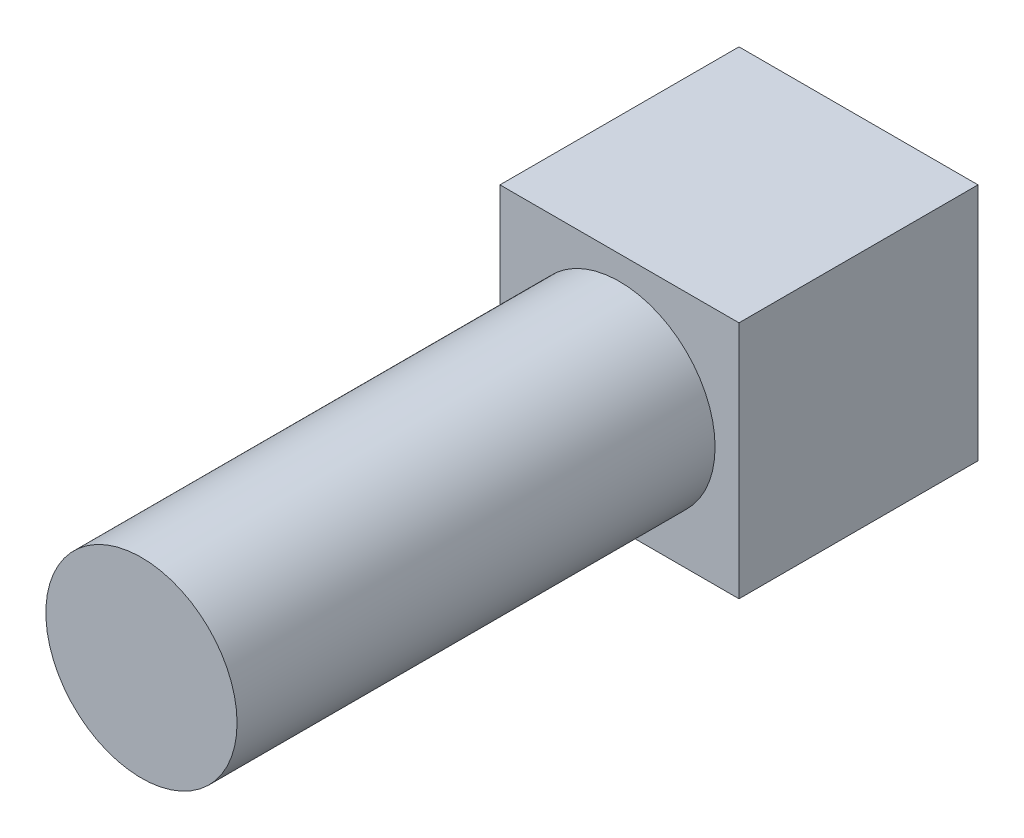
SolidWorks part; units mm, degrees
ref_plane "Front Plane" through (0, 0, 0) normal (0, 0, 1) x (1, 0, 0)
ref_plane "Top Plane" through (0, 0, 0) normal (0, 1, 0) x (1, 0, 0)
ref_plane "Right Plane" through (0, 0, 0) normal (1, 0, 0) x (0, 0, -1)
sketch "Sketch1" plane through (0, 0, 0) normal (0, 1, 0) x (1, 0, 0)
  line L1 (-5, 5) -> (5, 5)
  line L2 (-5, 5) -> (-5, -5)
  line L3 (-5, -5) -> (5, -5)
  line L4 (5, 5) -> (5, -5)
  line L5 (-5, 5) -> (5, -5) construction
  line L6 (-5, -5) -> (5, 5) construction
  point P0 (0, 0)
  dimension "D1" = 10
  dimension "D2" = 10
extrude "Boss-Extrude1" add sketch "Sketch1" along normal blind 10
sketch "Sketch2" plane through (0, 0, 5) normal (0, 0, 1) x (1, 0, 0)
  circle A1 centre (0, 5) radius 4
  dimension "D1" = 5
extrude "Boss-Extrude2" add sketch "Sketch2" along normal blind 20
